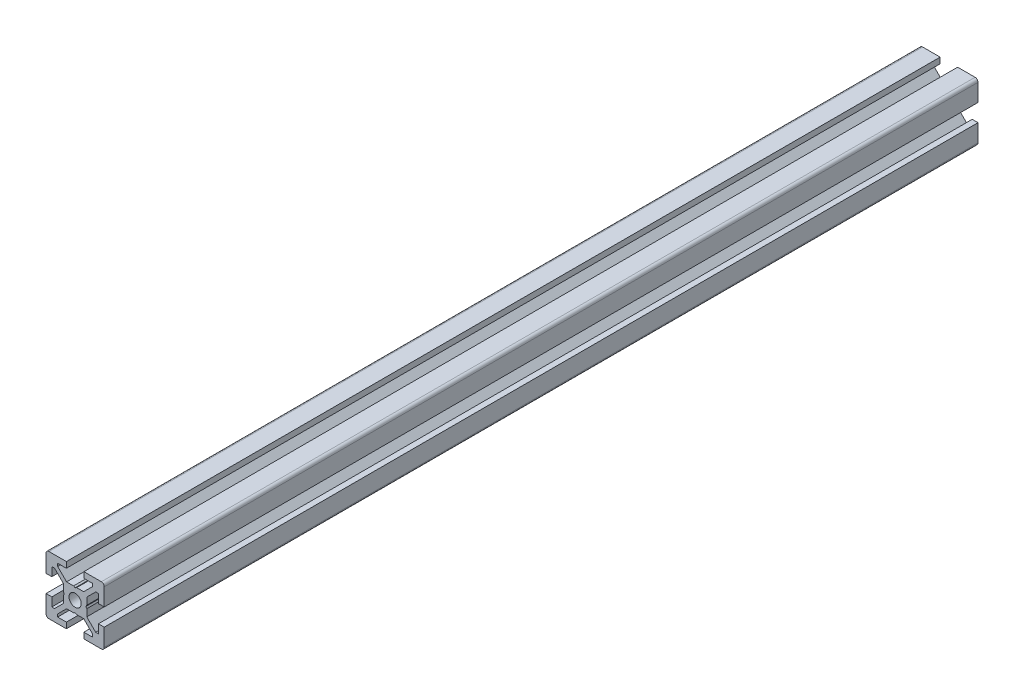
SolidWorks part; units mm, degrees
ref_plane "Front Plane" through (0, 0, 0) normal (0, 0, 1) x (1, 0, 0)
ref_plane "Top Plane" through (0, 0, 0) normal (0, 1, 0) x (1, 0, 0)
ref_plane "Right Plane" through (0, 0, 0) normal (1, 0, 0) x (0, 0, -1)
ref_plane "Plane1" through (0, 0, -340) normal (0, 0, -1) x (-1, 0, 0)
sketch "Sketch1" plane through (0, 0, -340) normal (0, 0, -1) x (-1, 0, 0)
  line L0 (10, -3) -> (8, -3)
  line L1 (8, -3) -> (8, -6)
  line L2 (8, -6) -> (7.0607, -6)
  line L3 (7.0607, -6) -> (4, -2.9393)
  line L4 (4, -2.9393) -> (4, -0.5196)
  line L5 (4, -0.5196) -> (3.7, 0)
  line L6 (3.7, 0) -> (4, 0.5196)
  line L7 (4, 0.5196) -> (4, 2.9393)
  line L8 (4, 2.9393) -> (7.0607, 6)
  line L9 (7.0607, 6) -> (8, 6)
  line L10 (8, 6) -> (8, 3)
  line L11 (8, 3) -> (10, 3)
  line L12 (10, 3) -> (10, 9)
  line L13 (9, 10) -> (3, 10)
  line L14 (3, 10) -> (3, 8)
  line L15 (3, 8) -> (6, 8)
  line L16 (6, 8) -> (6, 7.0607)
  line L17 (6, 7.0607) -> (2.9393, 4)
  line L18 (2.9393, 4) -> (0.5196, 4)
  line L19 (0.5196, 4) -> (0, 3.7)
  line L20 (0, 3.7) -> (-0.5196, 4)
  line L21 (-0.5196, 4) -> (-2.9393, 4)
  line L22 (-2.9393, 4) -> (-6, 7.0607)
  line L23 (-6, 7.0607) -> (-6, 8)
  line L24 (-6, 8) -> (-3, 8)
  line L25 (-3, 8) -> (-3, 10)
  line L26 (-3, 10) -> (-9, 10)
  line L27 (-10, 9) -> (-10, 3)
  line L28 (-10, 3) -> (-8, 3)
  line L29 (-8, 3) -> (-8, 6)
  line L30 (-8, 6) -> (-7.0607, 6)
  line L31 (-7.0607, 6) -> (-4, 2.9393)
  line L32 (-4, 2.9393) -> (-4, 0.5196)
  line L33 (-4, 0.5196) -> (-3.7, 0)
  line L34 (-3.7, 0) -> (-4, -0.5196)
  line L35 (-4, -0.5196) -> (-4, -2.9393)
  line L36 (-4, -2.9393) -> (-7.0607, -6)
  line L37 (-7.0607, -6) -> (-8, -6)
  line L38 (-8, -6) -> (-8, -3)
  line L39 (-8, -3) -> (-10, -3)
  line L40 (-10, -3) -> (-10, -9)
  line L41 (-9, -10) -> (-3, -10)
  line L42 (-3, -10) -> (-3, -8)
  line L43 (-3, -8) -> (-6, -8)
  line L44 (-6, -8) -> (-6, -7.0607)
  line L45 (-6, -7.0607) -> (-2.9393, -4)
  line L46 (-2.9393, -4) -> (-0.5196, -4)
  line L47 (-0.5196, -4) -> (0, -3.7)
  line L48 (0, -3.7) -> (0.5196, -4)
  line L49 (0.5196, -4) -> (2.9393, -4)
  line L50 (2.9393, -4) -> (6, -7.0607)
  line L51 (6, -7.0607) -> (6, -8)
  line L52 (6, -8) -> (3, -8)
  line L53 (3, -8) -> (3, -10)
  line L54 (3, -10) -> (9, -10)
  line L55 (10, -9) -> (10, -3)
  circle A0 centre (0, 0) radius 2.1
  arc A1 (10, 9) -> (9, 10) centre (9, 9) ccw
  arc A2 (-9, 10) -> (-10, 9) centre (-9, 9) ccw
  arc A3 (-10, -9) -> (-9, -10) centre (-9, -9) ccw
  arc A4 (9, -10) -> (10, -9) centre (9, -9) ccw
extrude "Boss-Extrude1" add sketch "Sketch1" against normal blind 300
